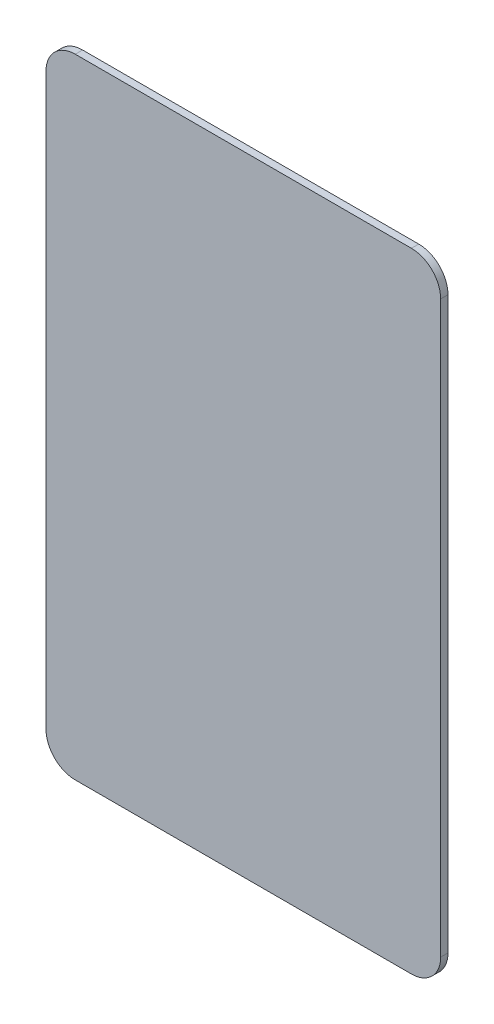
SolidWorks part; units mm, degrees
ref_plane "Front Plane" through (0, 0, 0) normal (0, 0, 1) x (1, 0, 0)
ref_plane "Top Plane" through (0, 0, 0) normal (0, 1, 0) x (1, 0, 0)
ref_plane "Right Plane" through (0, 0, 0) normal (1, 0, 0) x (0, 0, -1)
sketch "Sketch1" plane through (0, 0, 0) normal (0, 0, 1) x (1, 0, 0)
  line L1 (-27, -43) -> (27, -43)
  line L2 (-27, -43) -> (-27, 43)
  line L3 (-27, 43) -> (27, 43)
  line L4 (27, -43) -> (27, 43)
  line L5 (-27, -43) -> (27, 43) construction
  line L6 (-27, 43) -> (27, -43) construction
  point P0 (0, 0)
  dimension "D1" = 54
  dimension "D2" = 86
extrude "Boss-Extrude1" add sketch "Sketch1" along normal blind 1
fillet "Fillet1" radius 4 4 edges at (-27, -43, 0.5) (27, -43, 0.5) (27, 43, 0.5) (-27, 43, 0.5)
